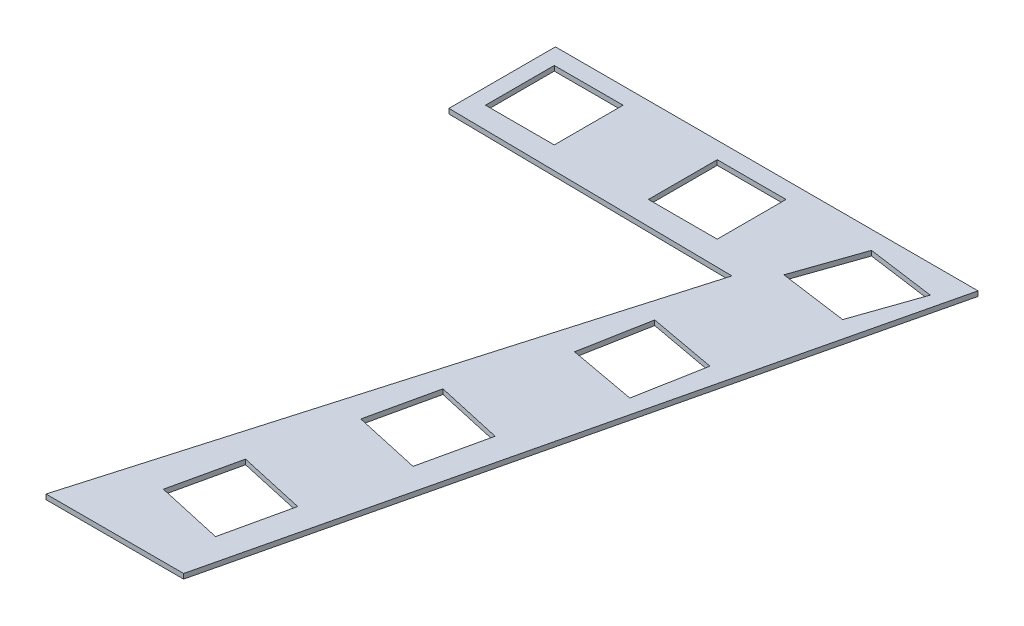
SolidWorks part; units mm, degrees
ref_plane "Front Plane" through (0, 0, 0) normal (0, 0, 1) x (1, 0, 0)
ref_plane "Top Plane" through (0, 0, 0) normal (0, 1, 0) x (1, 0, 0)
ref_plane "Right Plane" through (0, 0, 0) normal (1, 0, 0) x (0, 0, -1)
sketch "Sketch1" plane through (0, 0, 0) normal (0, 1, 0) x (1, 0, 0)
  line L0 (-16.1749, 86.3075) -> (69.8051, 86.3075)
  line L1 (69.8051, 86.3075) -> (38.7928, -44.3217)
  line L7 (38.7928, -44.3217) -> (10.7928, -44.3217)
  line L8 (10.7928, -44.3217) -> (42.1451, 63.8983)
  line L10 (42.1451, 63.8983) -> (-16.1749, 64.6375)
  line L11 (-16.1749, 86.3075) -> (-16.1749, 64.6375)
  point P2 (0, 0)
  dimension "D1" = 85.98
  dimension "D2" = 21.67
  dimension "D3" = 28
  dimension "D4" = 134.26
  dimension "D5" = 112.67
  dimension "D6" = 58.32
extrude "Boss-Extrude1" add sketch "Sketch1" along normal blind 1 contours L1 L7 L8 L10 L11 L0
sketch "Sketch2" plane through (0, 0, 0) normal (0, 1, 0) x (1, 0, 0)
  line L4 (-13.0142, 82.9076) -> (-13.0142, 68.9076)
  line L5 (-13.0142, 68.9076) -> (0.9858, 68.9076)
  line L6 (0.9858, 68.9076) -> (0.9858, 82.9076)
  line L7 (0.9858, 82.9076) -> (-13.0142, 82.9076)
  line L9 (20.1687, 82.8804) -> (20.1687, 68.8804)
  line L10 (20.1687, 68.8804) -> (34.1687, 68.8804)
  line L11 (34.1687, 68.8804) -> (34.1687, 82.8804)
  line L12 (34.1687, 82.8804) -> (20.1687, 82.8804)
  line L18 (47.2353, 69.3798) -> (61.1043, 67.4692)
  line L19 (61.1043, 67.4692) -> (65.7053, 80.6916)
  line L20 (65.7053, 80.6916) -> (51.8363, 82.6022)
  line L21 (51.8363, 82.6022) -> (47.2353, 69.3798)
extrude "Cut-Extrude1" cut sketch "Sketch2" along normal through all
sketch "Sketch3" plane through (0, 1, 0) normal (0, 1, 0) x (1, 0, 0)
  line L0 (42.0398, 48.2909) -> (55.8088, 45.7586)
  line L4 (55.8088, 45.7586) -> (53.2765, 31.9895)
  line L5 (53.2765, 31.9895) -> (39.5075, 34.5218)
  line L6 (39.5075, 34.5218) -> (42.0398, 48.2909)
  line L10 (46.3027, 11.5566) -> (43.26, -2.1088)
  line L11 (43.26, -2.1088) -> (29.5946, 0.934)
  line L12 (29.5946, 0.934) -> (32.6373, 14.5993)
  line L13 (32.6373, 14.5993) -> (46.3027, 11.5566)
  line L16 (38.6014, -20.916) -> (35.5468, -34.5787)
  line L17 (35.5468, -34.5787) -> (21.8841, -31.5241)
  line L18 (21.8841, -31.5241) -> (24.9387, -17.8614)
  line L19 (24.9387, -17.8614) -> (38.6014, -20.916)
extrude "Cut-Extrude2" cut sketch "Sketch3" against normal through all
